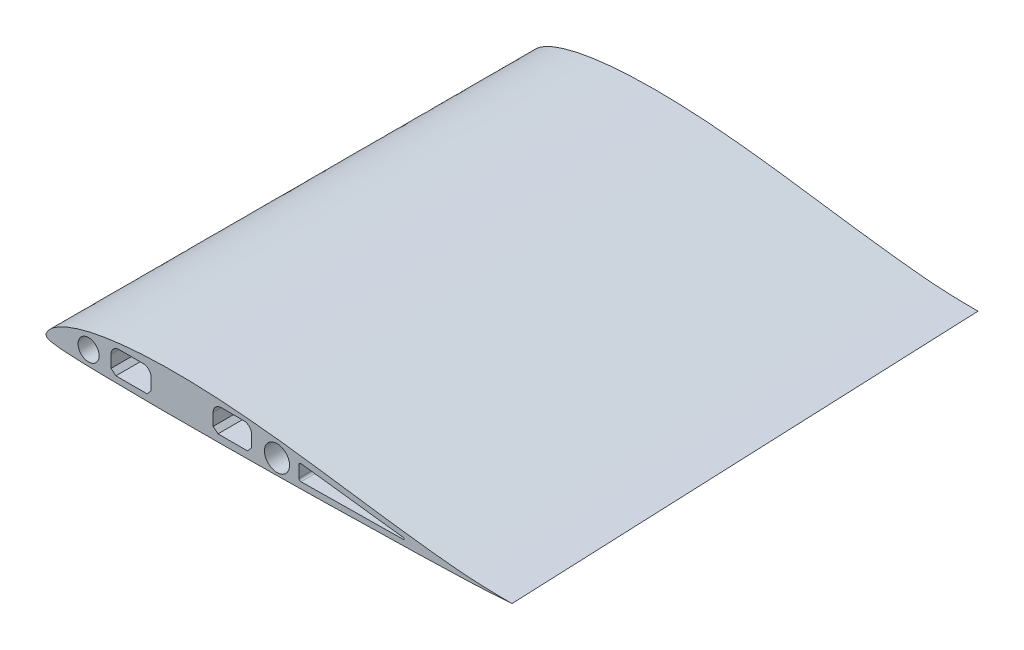
SolidWorks part; units mm, degrees
ref_plane "Front Plane" through (0, 0, 0) normal (0, 0, 1) x (1, 0, 0)
ref_plane "Top Plane" through (0, 0, 0) normal (0, 1, 0) x (1, 0, 0)
ref_plane "Right Plane" through (0, 0, 0) normal (1, 0, 0) x (0, 0, -1)
curve "Curve1"
  spline degree 3 poles (114.2372, -0.0369, 0) (115.1931, 0.0052, 0) (114.2229, -0.0046, 0) (113.4181, 0.0003, 0) (111.4454, 0.0187, 0) (108.9994, 0.0806, 0) (105.7801, 0.2031, 0) (101.978, 0.4673, 0) (97.6315, 0.881, 0) (92.8438, 1.4274, 0) (87.693, 2.0622, 0) (82.2613, 2.7949, 0) (76.6289, 3.5822, 0) (70.8754, 4.4083, 0) (65.0695, 5.2045, 0) (59.2726, 5.965, 0) (53.5354, 6.6121, 0) (47.902, 7.1479, 0) (42.4207, 7.5381, 0) (37.1257, 7.7843, 0) (32.0601, 7.8639, 0) (27.2609, 7.7997, 0) (22.7643, 7.5854, 0) (18.6066, 7.224, 0) (14.8196, 6.7174, 0) (11.4312, 6.1029, 0) (8.4633, 5.3595, 0) (5.93, 4.5232, 0) (3.8402, 3.6114, 0) (2.2031, 2.6805, 0) (0.9971, 1.7194, 0) (0.3061, 0.8447, 0) (-0.1539, -0.0168, 0) (0.4411, -0.7838, 0) (1.6303, -0.9762, 0) (3.345, -1.2471, 0) (5.7413, -1.3854, 0) (8.741, -1.531, 0) (12.3236, -1.6134, 0) (16.4261, -1.712, 0) (20.9966, -1.764, 0) (25.9799, -1.8041, 0) (31.3167, -1.8262, 0) (36.95, -1.8119, 0) (42.8101, -1.7838, 0) (48.8334, -1.73, 0) (54.9501, -1.6735, 0) (61.0935, -1.5952, 0) (67.1933, -1.4881, 0) (73.1769, -1.3978, 0) (78.98, -1.2712, 0) (84.5334, -1.153, 0) (89.7769, -1.0374, 0) (94.647, -0.905, 0) (99.0896, -0.7783, 0) (103.0556, -0.6463, 0) (106.4883, -0.5296, 0) (109.3913, -0.3707, 0) (111.629, -0.2442, 0) (113.4671, -0.0996, 0) (114.2372, -0.0369, 0) (115.1931, 0.0052, 0) (114.2229, -0.0046, 0) knots -0.013468 -0.006107 -0.001548 0 0.001545 0.006224 0.014036 0.024855 0.038644 0.055164 0.074045 0.09482 0.117223 0.140866 0.165395 0.190452 0.21571 0.240854 0.265734 0.290048 0.313714 0.336486 0.358293 0.37894 0.398278 0.416247 0.43266 0.44746 0.460566 0.472022 0.481784 0.489844 0.496307 0.501261 0.504695 0.507386 0.51219 0.519693 0.52998 0.542956 0.558414 0.576102 0.595805 0.617266 0.640272 0.664523 0.689804 0.715729 0.742084 0.768569 0.79484 0.82064 0.845625 0.869581 0.892164 0.91316 0.932311 0.949403 0.964221 0.976642 0.986532 0.993893 0.998452 1 1.001545 1.006224 1.014036 periodic
curve "Curve2"
  spline degree 3 poles (109.2695, -0.032, 0) (110.1862, 0.0049, 0) (109.2536, -0.0064, 0) (108.4853, 0.002, 0) (106.5995, 0.014, 0) (104.2599, 0.0712, 0) (101.179, 0.2009, 0) (97.5427, 0.452, 0) (93.3846, 0.8435, 0) (88.8052, 1.362, 0) (83.8804, 1.9786, 0) (78.6866, 2.6775, 0) (73.2995, 3.4307, 0) (67.7952, 4.2152, 0) (62.2412, 4.9847, 0) (56.6955, 5.6975, 0) (51.2078, 6.3228, 0) (45.8215, 6.8336, 0) (40.5778, 7.2116, 0) (35.5143, 7.4443, 0) (30.6685, 7.5275, 0) (26.0768, 7.4635, 0) (21.7757, 7.2552, 0) (17.7989, 6.9092, 0) (14.177, 6.4302, 0) (10.9351, 5.832, 0) (8.0947, 5.1223, 0) (5.6702, 4.3272, 0) (3.6698, 3.4606, 0) (2.1091, 2.5615, 0) (0.9527, 1.648, 0) (0.2925, 0.8103, 0) (-0.1445, -0.0134, 0) (0.4215, -0.7518, 0) (1.5614, -0.9277, 0) (3.1964, -1.1996, 0) (5.4899, -1.3252, 0) (8.3594, -1.4573, 0) (11.7865, -1.5532, 0) (15.712, -1.6328, 0) (20.0859, -1.6935, 0) (24.8533, -1.7305, 0) (29.9585, -1.7453, 0) (35.3441, -1.7366, 0) (40.949, -1.7075, 0) (46.7101, -1.6601, 0) (52.5621, -1.5957, 0) (58.4383, -1.5196, 0) (64.2724, -1.4291, 0) (69.9971, -1.3294, 0) (75.5481, -1.2224, 0) (80.8615, -1.1084, 0) (85.8767, -0.9906, 0) (90.5362, -0.8694, 0) (94.7848, -0.7467, 0) (98.5777, -0.6218, 0) (101.8584, -0.4962, 0) (104.6359, -0.3663, 0) (106.7737, -0.2243, 0) (108.5325, -0.0997, 0) (109.2695, -0.032, 0) (110.1862, 0.0049, 0) (109.2536, -0.0064, 0) knots -0.013463 -0.006118 -0.001552 0 0.001565 0.006239 0.014019 0.024861 0.03866 0.055174 0.074046 0.094837 0.117226 0.140856 0.165386 0.190451 0.215702 0.240867 0.265719 0.290052 0.313696 0.336484 0.35828 0.378929 0.398292 0.416236 0.43265 0.447456 0.460592 0.47203 0.481779 0.489853 0.496315 0.501246 0.504685 0.507404 0.512183 0.519673 0.529968 0.542948 0.5584 0.576099 0.595811 0.617283 0.64028 0.664535 0.689783 0.715733 0.742093 0.768567 0.794844 0.820639 0.845644 0.869584 0.892183 0.913178 0.932328 0.949411 0.96423 0.976629 0.986537 0.993882 0.998448 1 1.001565 1.006239 1.014019 periodic
sketch "Sketch1" plane through (0, 0, 0) normal (0, 0, 1) x (1, 0, 0)
  spline S0 degree 3 poles (114.2372, -0.0369) (115.1931, 0.0052) (114.2229, -0.0046) (113.4181, 0.0003) (111.4454, 0.0187) (108.9994, 0.0806) (105.7801, 0.2031) (101.978, 0.4673) (97.6315, 0.881) (92.8438, 1.4274) (87.693, 2.0622) (82.2613, 2.7949) (76.6289, 3.5822) (70.8754, 4.4083) (65.0695, 5.2045) (59.2726, 5.965) (53.5354, 6.6121) (47.902, 7.1479) (42.4207, 7.5381) (37.1257, 7.7843) (32.0601, 7.8639) (27.2609, 7.7997) (22.7643, 7.5854) (18.6066, 7.224) (14.8196, 6.7174) (11.4312, 6.1029) (8.4633, 5.3595) (5.93, 4.5232) (3.8402, 3.6114) (2.2031, 2.6805) (0.9971, 1.7194) (0.3061, 0.8447) (-0.1539, -0.0168) (0.4411, -0.7838) (1.6303, -0.9762) (3.345, -1.2471) (5.7413, -1.3854) (8.741, -1.531) (12.3236, -1.6134) (16.4261, -1.712) (20.9966, -1.764) (25.9799, -1.8041) (31.3167, -1.8262) (36.95, -1.8119) (42.8101, -1.7838) (48.8334, -1.73) (54.9501, -1.6735) (61.0935, -1.5952) (67.1933, -1.4881) (73.1769, -1.3978) (78.98, -1.2712) (84.5334, -1.153) (89.7769, -1.0374) (94.647, -0.905) (99.0896, -0.7783) (103.0556, -0.6463) (106.4883, -0.5296) (109.3913, -0.3707) (111.629, -0.2442) (113.4671, -0.0996) (114.2372, -0.0369) (115.1931, 0.0052) (114.2229, -0.0046) knots -0.013468 -0.006107 -0.001548 0 0.001545 0.006224 0.014036 0.024855 0.038644 0.055164 0.074045 0.09482 0.117223 0.140866 0.165395 0.190452 0.21571 0.240854 0.265734 0.290048 0.313714 0.336486 0.358293 0.37894 0.398278 0.416247 0.43266 0.44746 0.460566 0.472022 0.481784 0.489844 0.496307 0.501261 0.504695 0.507386 0.51219 0.519693 0.52998 0.542956 0.558414 0.576102 0.595805 0.617266 0.640272 0.664523 0.689804 0.715729 0.742084 0.768569 0.79484 0.82064 0.845625 0.869581 0.892164 0.91316 0.932311 0.949403 0.964221 0.976642 0.986532 0.993893 0.998452 1 1.001545 1.006224 1.014036 only from (115, 0) to (115, 0) construction
  spline S1 degree 3 poles (114.2372, -0.0369) (115.1931, 0.0052) (114.2229, -0.0046) (113.4181, 0.0003) (111.4454, 0.0187) (108.9994, 0.0806) (105.7801, 0.2031) (101.978, 0.4673) (97.6315, 0.881) (92.8438, 1.4274) (87.693, 2.0622) (82.2613, 2.7949) (76.6289, 3.5822) (70.8754, 4.4083) (65.0695, 5.2045) (59.2726, 5.965) (53.5354, 6.6121) (47.902, 7.1479) (42.4207, 7.5381) (37.1257, 7.7843) (32.0601, 7.8639) (27.2609, 7.7997) (22.7643, 7.5854) (18.6066, 7.224) (14.8196, 6.7174) (11.4312, 6.1029) (8.4633, 5.3595) (5.93, 4.5232) (3.8402, 3.6114) (2.2031, 2.6805) (0.9971, 1.7194) (0.3061, 0.8447) (-0.1539, -0.0168) (0.4411, -0.7838) (1.6303, -0.9762) (3.345, -1.2471) (5.7413, -1.3854) (8.741, -1.531) (12.3236, -1.6134) (16.4261, -1.712) (20.9966, -1.764) (25.9799, -1.8041) (31.3167, -1.8262) (36.95, -1.8119) (42.8101, -1.7838) (48.8334, -1.73) (54.9501, -1.6735) (61.0935, -1.5952) (67.1933, -1.4881) (73.1769, -1.3978) (78.98, -1.2712) (84.5334, -1.153) (89.7769, -1.0374) (94.647, -0.905) (99.0896, -0.7783) (103.0556, -0.6463) (106.4883, -0.5296) (109.3913, -0.3707) (111.629, -0.2442) (113.4671, -0.0996) (114.2372, -0.0369) (115.1931, 0.0052) (114.2229, -0.0046) knots -0.013468 -0.006107 -0.001548 0 0.001545 0.006224 0.014036 0.024855 0.038644 0.055164 0.074045 0.09482 0.117223 0.140866 0.165395 0.190452 0.21571 0.240854 0.265734 0.290048 0.313714 0.336486 0.358293 0.37894 0.398278 0.416247 0.43266 0.44746 0.460566 0.472022 0.481784 0.489844 0.496307 0.501261 0.504695 0.507386 0.51219 0.519693 0.52998 0.542956 0.558414 0.576102 0.595805 0.617266 0.640272 0.664523 0.689804 0.715729 0.742084 0.768569 0.79484 0.82064 0.845625 0.869581 0.892164 0.91316 0.932311 0.949403 0.964221 0.976642 0.986532 0.993893 0.998452 1 1.001545 1.006224 1.014036 only from (115, 0) to (115, 0)
ref_plane "Plane1" through (0, 0, -120) normal (0, 0, 1) x (1, 0, 0)
sketch "Sketch2" plane through (0, 0, -120) normal (0, 0, 1) x (1, 0, 0)
  spline S0 degree 3 poles (109.2695, -0.032) (110.1862, 0.0049) (109.2536, -0.0064) (108.4853, 0.002) (106.5995, 0.014) (104.2599, 0.0712) (101.179, 0.2009) (97.5427, 0.452) (93.3846, 0.8435) (88.8052, 1.362) (83.8804, 1.9786) (78.6866, 2.6775) (73.2995, 3.4307) (67.7952, 4.2152) (62.2412, 4.9847) (56.6955, 5.6975) (51.2078, 6.3228) (45.8215, 6.8336) (40.5778, 7.2116) (35.5143, 7.4443) (30.6685, 7.5275) (26.0768, 7.4635) (21.7757, 7.2552) (17.7989, 6.9092) (14.177, 6.4302) (10.9351, 5.832) (8.0947, 5.1223) (5.6702, 4.3272) (3.6698, 3.4606) (2.1091, 2.5615) (0.9527, 1.648) (0.2925, 0.8103) (-0.1445, -0.0134) (0.4215, -0.7518) (1.5614, -0.9277) (3.1964, -1.1996) (5.4899, -1.3252) (8.3594, -1.4573) (11.7865, -1.5532) (15.712, -1.6328) (20.0859, -1.6935) (24.8533, -1.7305) (29.9585, -1.7453) (35.3441, -1.7366) (40.949, -1.7075) (46.7101, -1.6601) (52.5621, -1.5957) (58.4383, -1.5196) (64.2724, -1.4291) (69.9971, -1.3294) (75.5481, -1.2224) (80.8615, -1.1084) (85.8767, -0.9906) (90.5362, -0.8694) (94.7848, -0.7467) (98.5777, -0.6218) (101.8584, -0.4962) (104.6359, -0.3663) (106.7737, -0.2243) (108.5325, -0.0997) (109.2695, -0.032) (110.1862, 0.0049) (109.2536, -0.0064) knots -0.013463 -0.006118 -0.001552 0 0.001565 0.006239 0.014019 0.024861 0.03866 0.055174 0.074046 0.094837 0.117226 0.140856 0.165386 0.190451 0.215702 0.240867 0.265719 0.290052 0.313696 0.336484 0.35828 0.378929 0.398292 0.416236 0.43265 0.447456 0.460592 0.47203 0.481779 0.489853 0.496315 0.501246 0.504685 0.507404 0.512183 0.519673 0.529968 0.542948 0.5584 0.576099 0.595811 0.617283 0.64028 0.664535 0.689783 0.715733 0.742093 0.768567 0.794844 0.820639 0.845644 0.869584 0.892183 0.913178 0.932328 0.949411 0.96423 0.976629 0.986537 0.993882 0.998448 1 1.001565 1.006239 1.014019 only from (110, 0) to (110, 0) construction
  spline S1 degree 3 poles (109.2695, -0.032) (110.1862, 0.0049) (109.2536, -0.0064) (108.4853, 0.002) (106.5995, 0.014) (104.2599, 0.0712) (101.179, 0.2009) (97.5427, 0.452) (93.3846, 0.8435) (88.8052, 1.362) (83.8804, 1.9786) (78.6866, 2.6775) (73.2995, 3.4307) (67.7952, 4.2152) (62.2412, 4.9847) (56.6955, 5.6975) (51.2078, 6.3228) (45.8215, 6.8336) (40.5778, 7.2116) (35.5143, 7.4443) (30.6685, 7.5275) (26.0768, 7.4635) (21.7757, 7.2552) (17.7989, 6.9092) (14.177, 6.4302) (10.9351, 5.832) (8.0947, 5.1223) (5.6702, 4.3272) (3.6698, 3.4606) (2.1091, 2.5615) (0.9527, 1.648) (0.2925, 0.8103) (-0.1445, -0.0134) (0.4215, -0.7518) (1.5614, -0.9277) (3.1964, -1.1996) (5.4899, -1.3252) (8.3594, -1.4573) (11.7865, -1.5532) (15.712, -1.6328) (20.0859, -1.6935) (24.8533, -1.7305) (29.9585, -1.7453) (35.3441, -1.7366) (40.949, -1.7075) (46.7101, -1.6601) (52.5621, -1.5957) (58.4383, -1.5196) (64.2724, -1.4291) (69.9971, -1.3294) (75.5481, -1.2224) (80.8615, -1.1084) (85.8767, -0.9906) (90.5362, -0.8694) (94.7848, -0.7467) (98.5777, -0.6218) (101.8584, -0.4962) (104.6359, -0.3663) (106.7737, -0.2243) (108.5325, -0.0997) (109.2695, -0.032) (110.1862, 0.0049) (109.2536, -0.0064) knots -0.013463 -0.006118 -0.001552 0 0.001565 0.006239 0.014019 0.024861 0.03866 0.055174 0.074046 0.094837 0.117226 0.140856 0.165386 0.190451 0.215702 0.240867 0.265719 0.290052 0.313696 0.336484 0.35828 0.378929 0.398292 0.416236 0.43265 0.447456 0.460592 0.47203 0.481779 0.489853 0.496315 0.501246 0.504685 0.507404 0.512183 0.519673 0.529968 0.542948 0.5584 0.576099 0.595811 0.617283 0.64028 0.664535 0.689783 0.715733 0.742093 0.768567 0.794844 0.820639 0.845644 0.869584 0.892183 0.913178 0.932328 0.949411 0.96423 0.976629 0.986537 0.993882 0.998448 1 1.001565 1.006239 1.014019 only from (110, 0) to (110, 0)
loft "Loft1" add profiles "Sketch1", "Sketch2"
sketch3d "3DSketch1"
  line L0 (109.9585, -0.0034, -120) -> (0.0473, 0.2989, -120)
  spline S0 degree 3 poles (0.0473, 0.2989, -120) (-0.0249, -1.826, -86.6776) (-0.0227, 5.1256, -127.705) (0.056, 12.511, -112.5454) knots 0 0 0 0 1 1 1 1
  spline S1 degree 3 poles (109.2695, -0.032, -120) (110.1862, 0.0049, -120) (109.2536, -0.0064, -120) (108.4853, 0.002, -120) (106.5995, 0.014, -120) (104.2599, 0.0712, -120) (101.179, 0.2009, -120) (97.5427, 0.452, -120) (93.3846, 0.8435, -120) (88.8052, 1.362, -120) (83.8804, 1.9786, -120) (78.6866, 2.6775, -120) (73.2995, 3.4307, -120) (67.7952, 4.2152, -120) (62.2412, 4.9847, -120) (56.6955, 5.6975, -120) (51.2078, 6.3228, -120) (45.8215, 6.8336, -120) (40.5778, 7.2116, -120) (35.5143, 7.4443, -120) (30.6685, 7.5275, -120) (26.0768, 7.4635, -120) (21.7757, 7.2552, -120) (17.7989, 6.9092, -120) (14.177, 6.4302, -120) (10.9351, 5.832, -120) (8.0947, 5.1223, -120) (5.6702, 4.3272, -120) (3.6698, 3.4606, -120) (2.1091, 2.5615, -120) (0.9527, 1.648, -120) (0.2925, 0.8103, -120) (-0.1445, -0.0134, -120) (0.4215, -0.7518, -120) (1.5614, -0.9277, -120) (3.1964, -1.1996, -120) (5.4899, -1.3252, -120) (8.3594, -1.4573, -120) (11.7865, -1.5532, -120) (15.712, -1.6328, -120) (20.0859, -1.6935, -120) (24.8533, -1.7305, -120) (29.9585, -1.7453, -120) (35.3441, -1.7366, -120) (40.949, -1.7075, -120) (46.7101, -1.6601, -120) (52.5621, -1.5957, -120) (58.4383, -1.5196, -120) (64.2724, -1.4291, -120) (69.9971, -1.3294, -120) (75.5481, -1.2224, -120) (80.8615, -1.1084, -120) (85.8767, -0.9906, -120) (90.5362, -0.8694, -120) (94.7848, -0.7467, -120) (98.5777, -0.6218, -120) (101.8584, -0.4962, -120) (104.6359, -0.3663, -120) (106.7737, -0.2243, -120) (108.5325, -0.0997, -120) (109.2695, -0.032, -120) (110.1862, 0.0049, -120) (109.2536, -0.0064, -120) knots -0.013463 -0.006118 -0.001552 0 0.001565 0.006239 0.014019 0.024861 0.03866 0.055174 0.074046 0.094837 0.117226 0.140856 0.165386 0.190451 0.215702 0.240867 0.265719 0.290052 0.313696 0.336484 0.35828 0.378929 0.398292 0.416236 0.43265 0.447456 0.460592 0.47203 0.481779 0.489853 0.496315 0.501246 0.504685 0.507404 0.512183 0.519673 0.529968 0.542948 0.5584 0.576099 0.595811 0.617283 0.64028 0.664535 0.689783 0.715733 0.742093 0.768567 0.794844 0.820639 0.845644 0.869584 0.892183 0.913178 0.932328 0.949411 0.96423 0.976629 0.986537 0.993882 0.998448 1 1.001565 1.006239 1.014019 only from (110, 0, -120) to (110, 0, -120) construction
  spline S2 degree 3 poles (109.2695, -0.032, -120) (110.1862, 0.0049, -120) (109.2536, -0.0064, -120) (108.4853, 0.002, -120) (106.5995, 0.014, -120) (104.2599, 0.0712, -120) (101.179, 0.2009, -120) (97.5427, 0.452, -120) (93.3846, 0.8435, -120) (88.8052, 1.362, -120) (83.8804, 1.9786, -120) (78.6866, 2.6775, -120) (73.2995, 3.4307, -120) (67.7952, 4.2152, -120) (62.2412, 4.9847, -120) (56.6955, 5.6975, -120) (51.2078, 6.3228, -120) (45.8215, 6.8336, -120) (40.5778, 7.2116, -120) (35.5143, 7.4443, -120) (30.6685, 7.5275, -120) (26.0768, 7.4635, -120) (21.7757, 7.2552, -120) (17.7989, 6.9092, -120) (14.177, 6.4302, -120) (10.9351, 5.832, -120) (8.0947, 5.1223, -120) (5.6702, 4.3272, -120) (3.6698, 3.4606, -120) (2.1091, 2.5615, -120) (0.9527, 1.648, -120) (0.2925, 0.8103, -120) (-0.1445, -0.0134, -120) (0.4215, -0.7518, -120) (1.5614, -0.9277, -120) (3.1964, -1.1996, -120) (5.4899, -1.3252, -120) (8.3594, -1.4573, -120) (11.7865, -1.5532, -120) (15.712, -1.6328, -120) (20.0859, -1.6935, -120) (24.8533, -1.7305, -120) (29.9585, -1.7453, -120) (35.3441, -1.7366, -120) (40.949, -1.7075, -120) (46.7101, -1.6601, -120) (52.5621, -1.5957, -120) (58.4383, -1.5196, -120) (64.2724, -1.4291, -120) (69.9971, -1.3294, -120) (75.5481, -1.2224, -120) (80.8615, -1.1084, -120) (85.8767, -0.9906, -120) (90.5362, -0.8694, -120) (94.7848, -0.7467, -120) (98.5777, -0.6218, -120) (101.8584, -0.4962, -120) (104.6359, -0.3663, -120) (106.7737, -0.2243, -120) (108.5325, -0.0997, -120) (109.2695, -0.032, -120) (110.1862, 0.0049, -120) (109.2536, -0.0064, -120) knots -0.013463 -0.006118 -0.001552 0 0.001565 0.006239 0.014019 0.024861 0.03866 0.055174 0.074046 0.094837 0.117226 0.140856 0.165386 0.190451 0.215702 0.240867 0.265719 0.290052 0.313696 0.336484 0.35828 0.378929 0.398292 0.416236 0.43265 0.447456 0.460592 0.47203 0.481779 0.489853 0.496315 0.501246 0.504685 0.507404 0.512183 0.519673 0.529968 0.542948 0.5584 0.576099 0.595811 0.617283 0.64028 0.664535 0.689783 0.715733 0.742093 0.768567 0.794844 0.820639 0.845644 0.869584 0.892183 0.913178 0.932328 0.949411 0.96423 0.976629 0.986537 0.993882 0.998448 1 1.001565 1.006239 1.014019 only from (110, 0, -120) to (110, 0, -120) construction
  spline S3 degree 3 poles (0.056, 12.511, -112.5454) (36.7587, 17.2094, -112.9091) (72.3737, 14.4641, -114.505) (106.8822, 2.4299, -108.2168) knots 0 0 0 0 1 1 1 1
  spline S4 degree 2 poles (109.9585, -0.0034, -120) (114.7544, -2.6544, -97.7196) (106.8822, 2.4299, -108.2168) knots 0 0 0 1 1 1
  spline S5 degree 3 poles (0.0473, 0.2989, -120) (0.0044, 0.1811, -120) (-0.0517, -0.1345, -120) (0.4215, -0.7518, -120) (1.5614, -0.9277, -120) (3.1964, -1.1996, -120) (5.4899, -1.3252, -120) (8.3594, -1.4573, -120) (11.7865, -1.5532, -120) (15.712, -1.6328, -120) (20.0859, -1.6935, -120) (24.8533, -1.7305, -120) (29.9585, -1.7453, -120) (35.3441, -1.7366, -120) (40.949, -1.7075, -120) (46.7101, -1.6601, -120) (52.5621, -1.5957, -120) (58.4383, -1.5196, -120) (64.2724, -1.4291, -120) (69.9971, -1.3294, -120) (75.5481, -1.2224, -120) (80.8615, -1.1084, -120) (85.8767, -0.9906, -120) (90.5362, -0.8694, -120) (94.7848, -0.7467, -120) (98.5777, -0.6218, -120) (101.8584, -0.4962, -120) (104.6359, -0.3663, -120) (106.7737, -0.2243, -120) (108.5325, -0.0997, -120) (109.2695, -0.032, -120) (110.1862, 0.0049, -120) (109.2536, -0.0064, -120) (108.895, -0.0025, -120) (108.5702, 0.0003, -120) (108.5502, 0.0005, -120) knots 0.50304 0.50304 0.50304 0.50304 0.504685 0.507404 0.512183 0.519673 0.529968 0.542948 0.5584 0.576099 0.595811 0.617283 0.64028 0.664535 0.689783 0.715733 0.742093 0.768567 0.794844 0.820639 0.845644 0.869584 0.892183 0.913178 0.932328 0.949411 0.96423 0.976629 0.986537 0.993882 0.998448 1 1.001565 1.006239 1.006543 1.006543 1.006543 1.006543
sketch "Sketch4" plane through (0, 0, 0) normal (0, 0, 1) x (1, 0, 0)
  circle A0 centre (10.5, 2) radius 2.6
  circle A1 centre (57, 2.1) radius 3.1
  dimension "D1" = 5.2
  dimension "D2" = 6.2
  dimension "D3" = 10.5
  dimension "D4" = 2
  dimension "D5" = 2.1
  dimension "D6" = 57
extrude "Cut-Extrude1" cut sketch "Sketch4" against normal blind 5.2
sketch "Sketch5" plane through (0, 0, 0) normal (0, 0, 1) x (1, 0, 0)
  line L1 (16.05, 5.8) -> (25.95, 5.8)
  line L2 (16.05, 5.8) -> (16.05, -0.2)
  line L3 (16.05, -0.2) -> (25.95, -0.2)
  line L4 (25.95, 5.8) -> (25.95, -0.2)
  line L5 (16.05, 5.8) -> (25.95, -0.2) construction
  line L6 (16.05, -0.2) -> (25.95, 5.8) construction
  line L7 (41.25, 6) -> (50.75, 6)
  line L8 (41.25, 6) -> (41.25, 0)
  line L9 (41.25, 0) -> (50.75, 0)
  line L10 (50.75, 6) -> (50.75, 0)
  line L11 (41.25, 6) -> (50.75, 0) construction
  line L12 (41.25, 0) -> (50.75, 6) construction
  point P0 (21, 2.8)
  point P5 (46, 3)
  dimension "D1" = 6
  dimension "D2" = 9.9
  dimension "D3" = 9.5
  dimension "D4" = 6
  dimension "D5" = 46
  dimension "D6" = 3
  dimension "D7" = 2.8
  dimension "D8" = 21
extrude "Cut-Extrude2" cut sketch "Sketch5" against normal blind 82
fillet "Fillet3" radius 2 4 edges at (50.75, 6, -41) (41.25, 6, -41) (25.95, 5.8, -41) (16.05, 5.8, -41)
chamfer "Chamfer1" distance 1 angle 50 4 edges at (50.75, 0, -41) (41.25, 0, -41) (25.95, -0.2, -41) (16.05, -0.2, -41)
sketch "Sketch6" plane through (0, 0, 0) normal (0, 0, 1) x (1, 0, 0)
  line L0 (62.4119, 3.9406) -> (62.4119, 0)
  line L3 (62.4119, 0) -> (91.1231, 0.3435)
  line L4 (91.1231, 0.3435) -> (62.4119, 3.9406)
  spline S1 degree 3 poles (114.2372, -0.0369) (115.1931, 0.0052) (114.2229, -0.0046) (113.4181, 0.0003) (111.4454, 0.0187) (108.9994, 0.0806) (105.7801, 0.2031) (101.978, 0.4673) (97.6315, 0.881) (92.8438, 1.4274) (87.693, 2.0622) (82.2613, 2.7949) (76.6289, 3.5822) (70.8754, 4.4083) (65.0695, 5.2045) (59.2726, 5.965) (53.5354, 6.6121) (47.902, 7.1479) (42.4207, 7.5381) (37.1257, 7.7843) (32.0601, 7.8639) (27.2609, 7.7997) (22.7643, 7.5854) (18.6066, 7.224) (14.8196, 6.7174) (11.4312, 6.1029) (8.4633, 5.3595) (5.93, 4.5232) (3.8402, 3.6114) (2.2031, 2.6805) (0.9971, 1.7194) (0.3061, 0.8447) (-0.1539, -0.0168) (0.4411, -0.7838) (1.6303, -0.9762) (3.345, -1.2471) (5.7413, -1.3854) (8.741, -1.531) (12.3236, -1.6134) (16.4261, -1.712) (20.9966, -1.764) (25.9799, -1.8041) (31.3167, -1.8262) (36.95, -1.8119) (42.8101, -1.7838) (48.8334, -1.73) (54.9501, -1.6735) (61.0935, -1.5952) (67.1933, -1.4881) (73.1769, -1.3978) (78.98, -1.2712) (84.5334, -1.153) (89.7769, -1.0374) (94.647, -0.905) (99.0896, -0.7783) (103.0556, -0.6463) (106.4883, -0.5296) (109.3913, -0.3707) (111.629, -0.2442) (113.4671, -0.0996) (114.2372, -0.0369) (115.1931, 0.0052) (114.2229, -0.0046) knots -0.013468 -0.006107 -0.001548 0 0.001545 0.006224 0.014036 0.024855 0.038644 0.055164 0.074045 0.09482 0.117223 0.140866 0.165395 0.190452 0.21571 0.240854 0.265734 0.290048 0.313714 0.336486 0.358293 0.37894 0.398278 0.416247 0.43266 0.44746 0.460566 0.472022 0.481784 0.489844 0.496307 0.501261 0.504695 0.507386 0.51219 0.519693 0.52998 0.542956 0.558414 0.576102 0.595805 0.617266 0.640272 0.664523 0.689804 0.715729 0.742084 0.768569 0.79484 0.82064 0.845625 0.869581 0.892164 0.91316 0.932311 0.949403 0.964221 0.976642 0.986532 0.993893 0.998452 1 1.001545 1.006224 1.014036 only from (115, 0) to (115, 0) construction
  spline S2 degree 3 poles (114.2372, -0.0369) (115.1931, 0.0052) (114.2229, -0.0046) (113.4181, 0.0003) (111.4454, 0.0187) (108.9994, 0.0806) (105.7801, 0.2031) (101.978, 0.4673) (97.6315, 0.881) (92.8438, 1.4274) (87.693, 2.0622) (82.2613, 2.7949) (76.6289, 3.5822) (70.8754, 4.4083) (65.0695, 5.2045) (59.2726, 5.965) (53.5354, 6.6121) (47.902, 7.1479) (42.4207, 7.5381) (37.1257, 7.7843) (32.0601, 7.8639) (27.2609, 7.7997) (22.7643, 7.5854) (18.6066, 7.224) (14.8196, 6.7174) (11.4312, 6.1029) (8.4633, 5.3595) (5.93, 4.5232) (3.8402, 3.6114) (2.2031, 2.6805) (0.9971, 1.7194) (0.3061, 0.8447) (-0.1539, -0.0168) (0.4411, -0.7838) (1.6303, -0.9762) (3.345, -1.2471) (5.7413, -1.3854) (8.741, -1.531) (12.3236, -1.6134) (16.4261, -1.712) (20.9966, -1.764) (25.9799, -1.8041) (31.3167, -1.8262) (36.95, -1.8119) (42.8101, -1.7838) (48.8334, -1.73) (54.9501, -1.6735) (61.0935, -1.5952) (67.1933, -1.4881) (73.1769, -1.3978) (78.98, -1.2712) (84.5334, -1.153) (89.7769, -1.0374) (94.647, -0.905) (99.0896, -0.7783) (103.0556, -0.6463) (106.4883, -0.5296) (109.3913, -0.3707) (111.629, -0.2442) (113.4671, -0.0996) (114.2372, -0.0369) (115.1931, 0.0052) (114.2229, -0.0046) knots -0.013468 -0.006107 -0.001548 0 0.001545 0.006224 0.014036 0.024855 0.038644 0.055164 0.074045 0.09482 0.117223 0.140866 0.165395 0.190452 0.21571 0.240854 0.265734 0.290048 0.313714 0.336486 0.358293 0.37894 0.398278 0.416247 0.43266 0.44746 0.460566 0.472022 0.481784 0.489844 0.496307 0.501261 0.504695 0.507386 0.51219 0.519693 0.52998 0.542956 0.558414 0.576102 0.595805 0.617266 0.640272 0.664523 0.689804 0.715729 0.742084 0.768569 0.79484 0.82064 0.845625 0.869581 0.892164 0.91316 0.932311 0.949403 0.964221 0.976642 0.986532 0.993893 0.998452 1 1.001545 1.006224 1.014036 only from (115, 0) to (115, 0)
extrude "Cut-Extrude3" cut sketch "Sketch6" against normal blind 90.2 contours L4 L0 L3
fillet "Fillet4" radius 0.2 1 edges at (91.1231, 0.3435, -45.1)
fillet "Fillet5" radius 0.5 2 edges at (62.4119, 0, -45.1) (62.4119, 3.9406, -45.1)
ref_plane "Plane2" through (0, 6, 0) normal (0, 1, 0) x (1, 0, 0)
